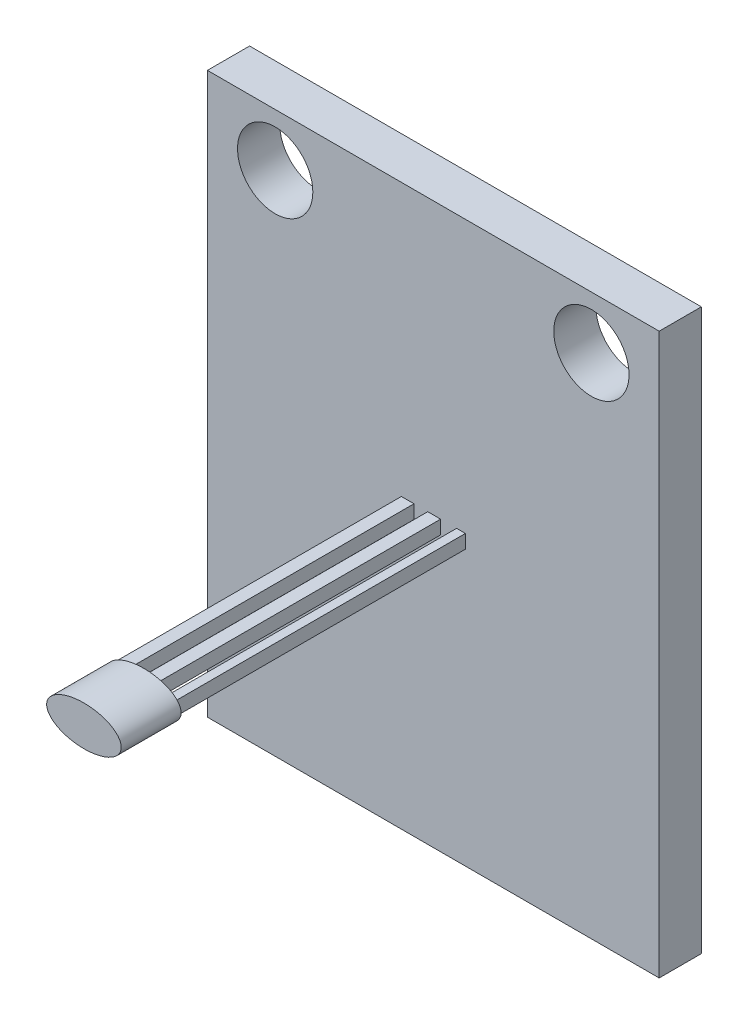
SolidWorks part; units mm, degrees
ref_plane "Front Plane" through (0, 0, 0) normal (0, 0, 1) x (1, 0, 0)
ref_plane "Top Plane" through (0, 0, 0) normal (0, 1, 0) x (1, 0, 0)
ref_plane "Right Plane" through (0, 0, 0) normal (1, 0, 0) x (0, 0, -1)
sketch "Sketch1" plane through (0, 0, 0) normal (0, 0, 1) x (1, 0, 0)
  line L0 (7.5, 18.6) -> (7.5, 0) construction
  line L1 (0, 0) -> (15, 0)
  line L2 (0, 0) -> (0, 18.6)
  line L3 (0, 18.6) -> (15, 18.6)
  line L4 (15, 0) -> (15, 18.6)
  circle A0 centre (2.25, 16.85) radius 1.25
  circle A1 centre (12.75, 16.85) radius 1.25
  dimension "D1" = 5.25
  dimension "D2" = 2.5
  dimension "D3" = 15
  dimension "D4" = 1.75
  dimension "D5" = 18.6
extrude "Boss-Extrude1" add sketch "Sketch1" along normal blind 1.4
sketch "Sketch3" plane through (0, 0, 1.4) normal (0, 0, 1) x (1, 0, 0)
  line L0 (0, 9.3) -> (15, 9.3) construction
  line L1 (0, 18.6) -> (0, 0) construction
  line L2 (15, 0) -> (15, 18.6) construction
  ellipse E0 centre (7.5, 9.3) end of major axis (6.262, 9.3) minor radius 0.6585
extrude "Boss-Extrude2" add sketch "Sketch3" along normal blind 11.6
sketch "Sketch4" plane through (0, 0, 0) normal (0, -1, 0) x (1, 0, 0)
  line L0 (0, 1.4) -> (15, 1.4) construction
  line L1 (6.8591, 11.0105) -> (7.3157, 11.0105)
  line L2 (6.8591, 11.0105) -> (6.8591, 1.4)
  line L3 (6.8591, 1.4) -> (7.3157, 1.4)
  line L4 (7.3157, 11.0105) -> (7.3157, 1.4)
  line L6 (7.7432, 11.0105) -> (8.2732, 11.0105)
  line L7 (7.7432, 11.0105) -> (7.7432, 1.4)
  line L8 (7.7432, 1.4) -> (8.2732, 1.4)
  line L9 (8.2732, 11.0105) -> (8.2732, 1.4)
  line L10 (6.4408, 11.0105) -> (3.9597, 11.0105)
  line L11 (6.4408, 11.0105) -> (6.4408, 1.4)
  line L12 (6.4408, 1.4) -> (3.9597, 1.4)
  line L13 (3.9597, 11.0105) -> (3.9597, 1.4)
  line L14 (8.5662, 11.0105) -> (11.4197, 11.0105)
  line L15 (8.5662, 11.0105) -> (8.5662, 1.4)
  line L16 (8.5662, 1.4) -> (11.4197, 1.4)
  line L17 (11.4197, 11.0105) -> (11.4197, 1.4)
extrude "Cut-Extrude1" cut sketch "Sketch4" against normal up to surface (18.6 mm away) up to face at (7.5, 18.6, 0.7)
sketch "Sketch5" plane through (0, 0, 0) normal (-1, 0, 0) x (0, 0, 1)
  line L0 (11.0105, 9.6409) -> (11.0105, 8.9591) construction
  line L1 (11.0105, 9.5667) -> (1.4, 9.5667)
  line L2 (11.0105, 9.5667) -> (11.0105, 14.0557)
  line L3 (11.0105, 14.0557) -> (1.4, 14.0557)
  line L4 (1.4, 9.5667) -> (1.4, 14.0557)
  line L5 (1.4, 18.6) -> (1.4, 0) construction
  line L6 (11.0105, 9.6409) -> (11.0105, 8.9591) construction
  line L7 (11.0105, 9.1133) -> (1.4, 9.1133)
  line L8 (11.0105, 9.1133) -> (11.0105, 6.6611)
  line L9 (11.0105, 6.6611) -> (1.4, 6.6611)
  line L10 (1.4, 9.1133) -> (1.4, 6.6611)
extrude "Cut-Extrude2" cut sketch "Sketch5" against normal up to surface (15 mm away) up to face at (15, 9.3, 0.7)
